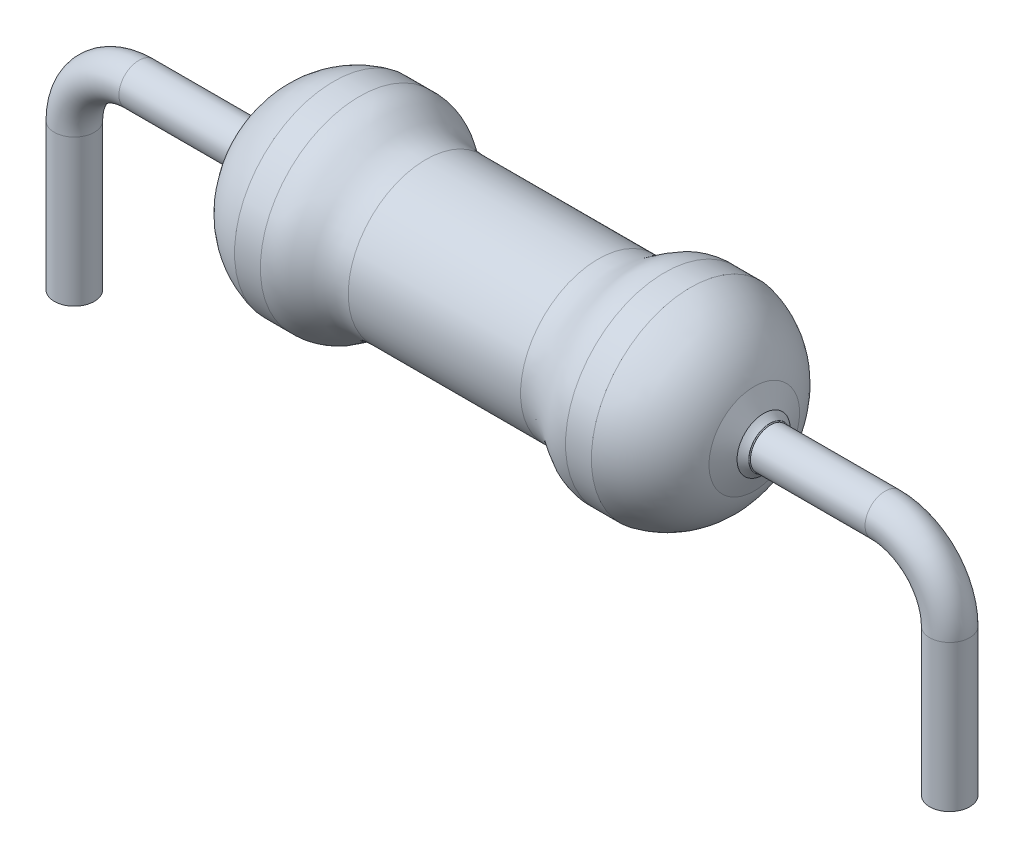
SolidWorks part; units mm, degrees
ref_plane "Спереди" through (0, 0, 0) normal (0, 0, 1) x (1, 0, 0)
ref_plane "Сверху" through (0, 0, 0) normal (0, 1, 0) x (1, 0, 0)
ref_plane "Справа" through (0, 0, 0) normal (1, 0, 0) x (0, 0, -1)
sketch "Эскиз1" plane through (0, 0, 0) normal (0, 0, 1) x (1, 0, 0)
  line L0 (0, -0.6264) -> (0, 2.3312) construction
  line L1 (3, 0.2403) -> (3, 0)
  line L2 (3, 0.2403) -> (2.9904, 0.2427)
  line L3 (2.8119, 0.5255) -> (2.9204, 0.3084)
  line L7 (2.0707, 1.15) -> (1.7707, 1.15)
  line L8 (3, 0) -> (-3, 0)
  line L27 (26.5292, 0) -> (-26.8628, 0) construction
  line L38 (-1, 0.9006) -> (1, 0.9006)
  line L39 (-2.0707, 1.15) -> (-1.7707, 1.15)
  line L46 (-2.8119, 0.5255) -> (-2.9204, 0.3084)
  line L47 (-3, 0.2403) -> (-2.9904, 0.2427)
  line L48 (-3, 0.2403) -> (-3, 0)
  arc A0 (2.9904, 0.2427) -> (2.9204, 0.3084) centre (3.2839, 0.6257) cw
  arc A1 (2.0707, 1.15) -> (2.8119, 0.5255) centre (1.8756, 0.1663) cw
  arc A11 (-2.0707, 1.15) -> (-2.8119, 0.5255) centre (-1.8756, 0.1663) ccw
  arc A12 (-2.9904, 0.2427) -> (-2.9204, 0.3084) centre (-3.2839, 0.6257) ccw
  spline S0 degree 3 poles (1.7707, 1.15) (1.3919, 1.1674) (1.3788, 0.8832) (1, 0.9006) knots 0 0 0 0 1 1 1 1
  spline S5 degree 3 poles (-1.7707, 1.15) (-1.3919, 1.1674) (-1.3788, 0.8832) (-1, 0.9006) knots 0 0 0 0 1 1 1 1
  point P8 (0, 0)
  point P29 (0, 0.9006)
  dimension "D1" = 0.3
  dimension "D2" = 1
  dimension "D3" = 1.15
  dimension "D4" = 3
revolve "Повернуть1" add sketch "Эскиз1" angle 360 about L27
fillet "Скругление2" radius 0.01 2 edges at (-3, 0, -0.2403) (3, 0, -0.2403)
sketch "Croquis5" plane through (3, 0, 0) normal (1, 0, 0) x (0, 0, -1)
  circle A1 centre (0, 0) radius 0.2325
  circle A2 centre (0, 0) radius 0.2325
  dimension "D1" = 0
sketch "Croquis6" plane through (0, 0, 0) normal (0, 0, 1) x (1, 0, 0)
  line L0 (3, 0) -> (4.33, 0)
  line L1 (3, -0.2325) -> (3, 0.2325) construction
  line L2 (5.08, -0.75) -> (5.08, -2.45)
  arc A0 (4.33, 0) -> (5.08, -0.75) centre (4.33, -0.75) cw
  dimension "D1" = 0.75
  dimension "D2" = 5.08
  dimension "D3" = 2.45
sweep "Barrer1" add profiles "Croquis5" path "Croquis6"
mirror "Simetría1" about plane through (0, 0, 0) normal (1, 0, 0) of "Barrer1"
